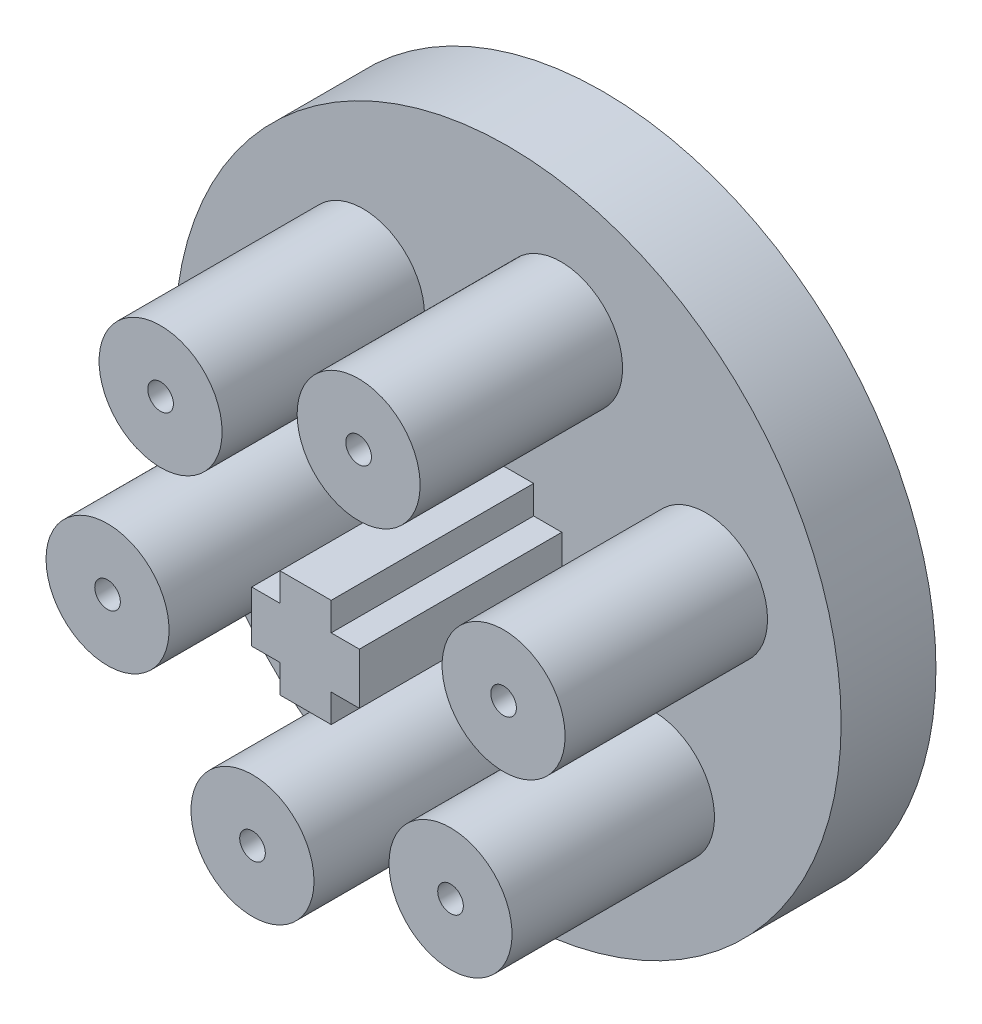
SolidWorks part; units mm, degrees
ref_plane "前视基准面" through (0, 0, 0) normal (0, 0, 1) x (1, 0, 0)
ref_plane "上视基准面" through (0, 0, 0) normal (0, 1, 0) x (1, 0, 0)
ref_plane "右视基准面" through (0, 0, 0) normal (1, 0, 0) x (0, 0, -1)
other "Configuration Table"
sketch "草图1" plane through (0, 0, 0) normal (0, 0, 1) x (1, 0, 0)
  circle A0 centre (0, 0) radius 13
  dimension "D1" = 26
extrude "凸台-拉伸1" add sketch "草图1" along normal blind 3.7 contours A0
sketch "草图2" plane through (0, 0, 3.7) normal (0, 0, 1) x (1, 0, 0)
  line L1 (-1, -2.1) -> (1, -2.1)
  line L2 (-1, -2.1) -> (-1, 2.1)
  line L3 (-1, 2.1) -> (1, 2.1)
  line L4 (1, -2.1) -> (1, 2.1)
  line L5 (-1, -2.1) -> (1, 2.1) construction
  line L6 (-1, 2.1) -> (1, -2.1) construction
  line L7 (-2.1, -1) -> (2.1, -1)
  line L8 (-2.1, -1) -> (-2.1, 1)
  line L9 (-2.1, 1) -> (2.1, 1)
  line L10 (2.1, -1) -> (2.1, 1)
  line L11 (-2.1, -1) -> (2.1, 1) construction
  line L12 (-2.1, 1) -> (2.1, -1) construction
  point P0 (0, 0)
  point P6 (0, 0)
  dimension "D1" = 2
  dimension "D2" = 4.2
extrude "凸台-拉伸2" add sketch "草图2" along normal blind 7.9 contours L7 L10 L9 L8 | L4 L3 L2 L1
sketch "草图3" plane through (0, 0, 3.7) normal (0, 0, 1) x (1, 0, 0)
  line L0 (0, 0) -> (0, 10.0172) construction
  line L1 (-5.6569, 5.6569) -> (0, 0) construction
  circle A0 centre (-5.6569, 5.6569) radius 2.4
  circle A1 centre (-5.6569, 5.6569) radius 0.5
  dimension "D1" = 4.8
  dimension "D3" = 1
  dimension "D2" = 8
  dimension "D4" = 45
extrude "凸台-拉伸3" add sketch "草图3" along normal blind 7.9
pattern_circular "阵列(圆周)1" count 6 over 360 about axis through (0, 0, 0) along (0, 0, 1) of "凸台-拉伸3"
